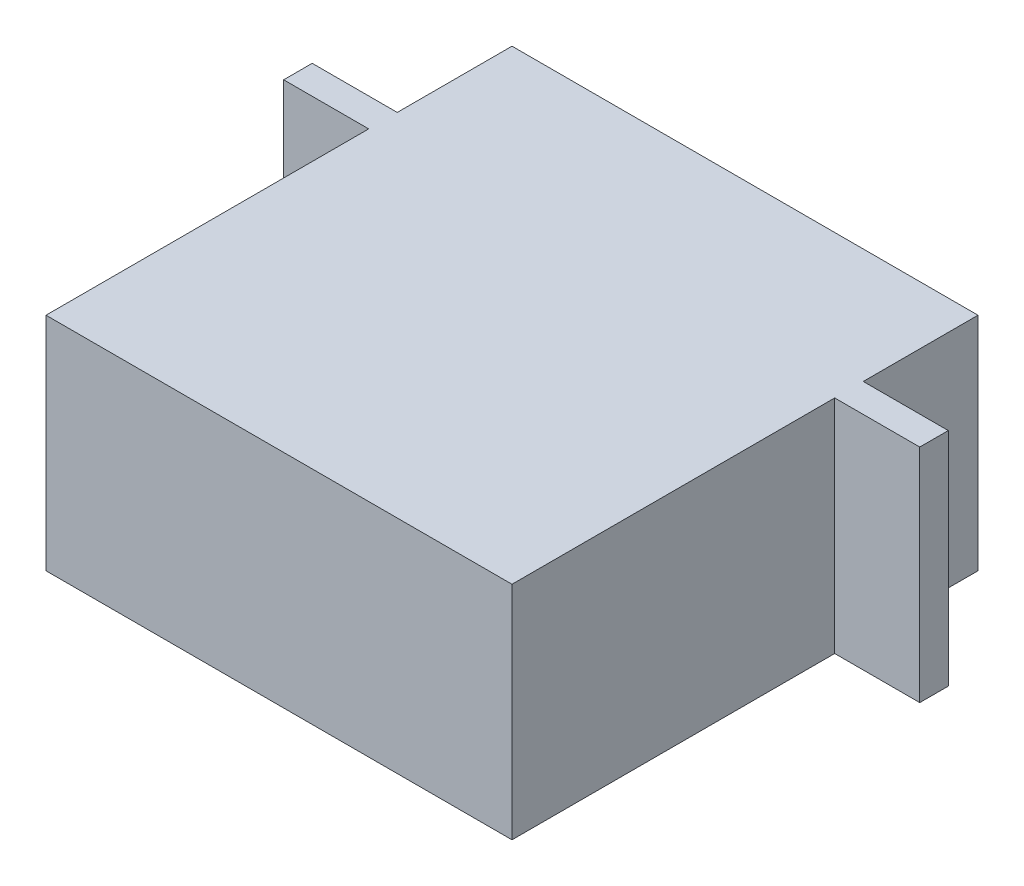
SolidWorks part; units mm, degrees
ref_plane "Спереди" through (0, 0, 0) normal (0, 0, 1) x (1, 0, 0)
ref_plane "Сверху" through (0, 0, 0) normal (0, 1, 0) x (1, 0, 0)
ref_plane "Справа" through (0, 0, 0) normal (1, 0, 0) x (0, 0, -1)
other "Configuration Table"
sketch "Эскиз1" plane through (0, 0, 0) normal (0, 1, 0) x (1, 0, 0)
  line L1 (-20, -20) -> (20, -20)
  line L2 (-20, -20) -> (-20, 20)
  line L3 (-20, 20) -> (20, 20)
  line L4 (20, -20) -> (20, 20)
  line L5 (-20, -20) -> (20, 20) construction
  line L6 (-20, 20) -> (20, -20) construction
  point P0 (0, 0)
  dimension "D1" = 40
  dimension "D2" = 40
extrude "Бобышка-Вытянуть1" add sketch "Эскиз1" along normal blind 19
sketch "Эскиз2" plane through (0, 0, -20) normal (0, 0, -1) x (-1, 0, 0)
  line L0 (-20, 19) -> (-20, 0) construction
  line L1 (-20, 19) -> (20, 19) construction
  circle A0 centre (-11, 10) radius 3
  dimension "D1" = 6
  dimension "D2" = 9
  dimension "D3" = 9
extrude "Бобышка-Вытянуть2" add sketch "Эскиз2" along normal blind 4
sketch "Эскиз3" plane through (20, 0, 0) normal (1, 0, 0) x (0, 0, -1)
  line L0 (-20, 19) -> (20, 19) construction
  line L1 (7.7, 0) -> (10.15, 0)
  line L2 (7.7, 0) -> (7.7, 19)
  line L3 (7.7, 19) -> (10.15, 19)
  line L4 (10.15, 0) -> (10.15, 19)
  line L5 (7.7, 0) -> (10.15, 19) construction
  line L6 (7.7, 19) -> (10.15, 0) construction
  line L7 (20, 19) -> (20, 0) construction
  point P0 (8.925, 9.5)
  dimension "D1" = 12.3
  dimension "D2" = 2.45
extrude "Бобышка-Вытянуть3" add sketch "Эскиз3" along normal blind 7.3
sketch "Эскиз5" plane through (-20, 0, 0) normal (-1, 0, 0) x (0, 0, 1)
  line L0 (-20, 19) -> (20, 19) construction
  line L1 (-10.15, 0) -> (-7.7, 0)
  line L2 (-10.15, 0) -> (-10.15, 19)
  line L3 (-10.15, 19) -> (-7.7, 19)
  line L4 (-7.7, 0) -> (-7.7, 19)
  line L5 (-10.15, 0) -> (-7.7, 19) construction
  line L6 (-10.15, 19) -> (-7.7, 0) construction
  line L8 (-20, 19) -> (-20, 0) construction
  point P0 (-8.925, 9.5)
  dimension "D1" = 2.45
  dimension "D2" = 12.3
extrude "Бобышка-Вытянуть4" add sketch "Эскиз5" along normal blind 7.3
sketch "Эскиз6" plane through (0, 0, 20) normal (0, 0, 1) x (1, 0, 0)
  line L0 (-20, 19) -> (20, 0)
  line L1 (20, 19) -> (-20, 0)
  point P8 (0, 9.5)
